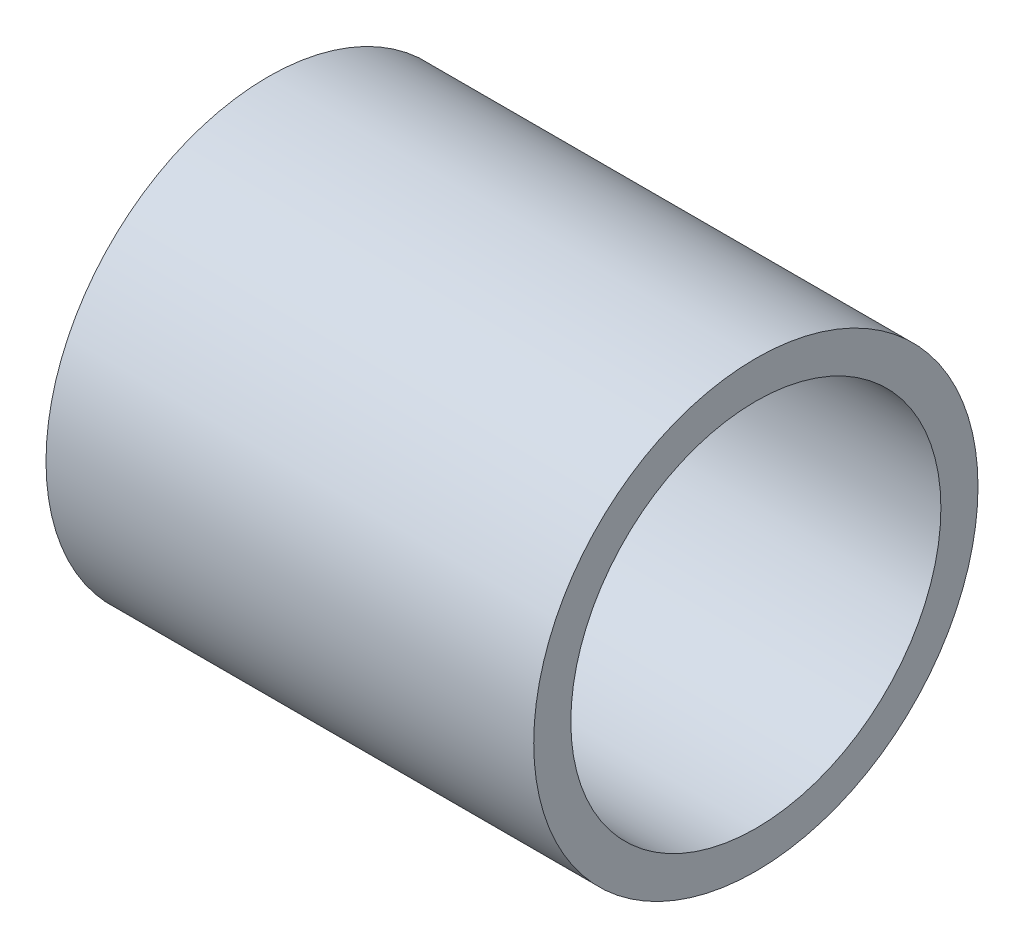
SolidWorks part; units mm, degrees
ref_plane "Front Plane" through (0, 0, 0) normal (0, 0, 1) x (1, 0, 0)
ref_plane "Top Plane" through (0, 0, 0) normal (0, 1, 0) x (1, 0, 0)
ref_plane "Right Plane" through (0, 0, 0) normal (1, 0, 0) x (0, 0, -1)
sketch "Sketch1" plane through (0, 0, 0) normal (1, 0, 0) x (0, 0, -1)
  circle A0 centre (0, 0) radius 2.65
  circle A1 centre (0, 0) radius 3.1813
  dimension "D1" = 5.3
  dimension "D2" = 6.3627
extrude "Boss-Extrude1" add sketch "Sketch1" along normal mid plane 6.985
